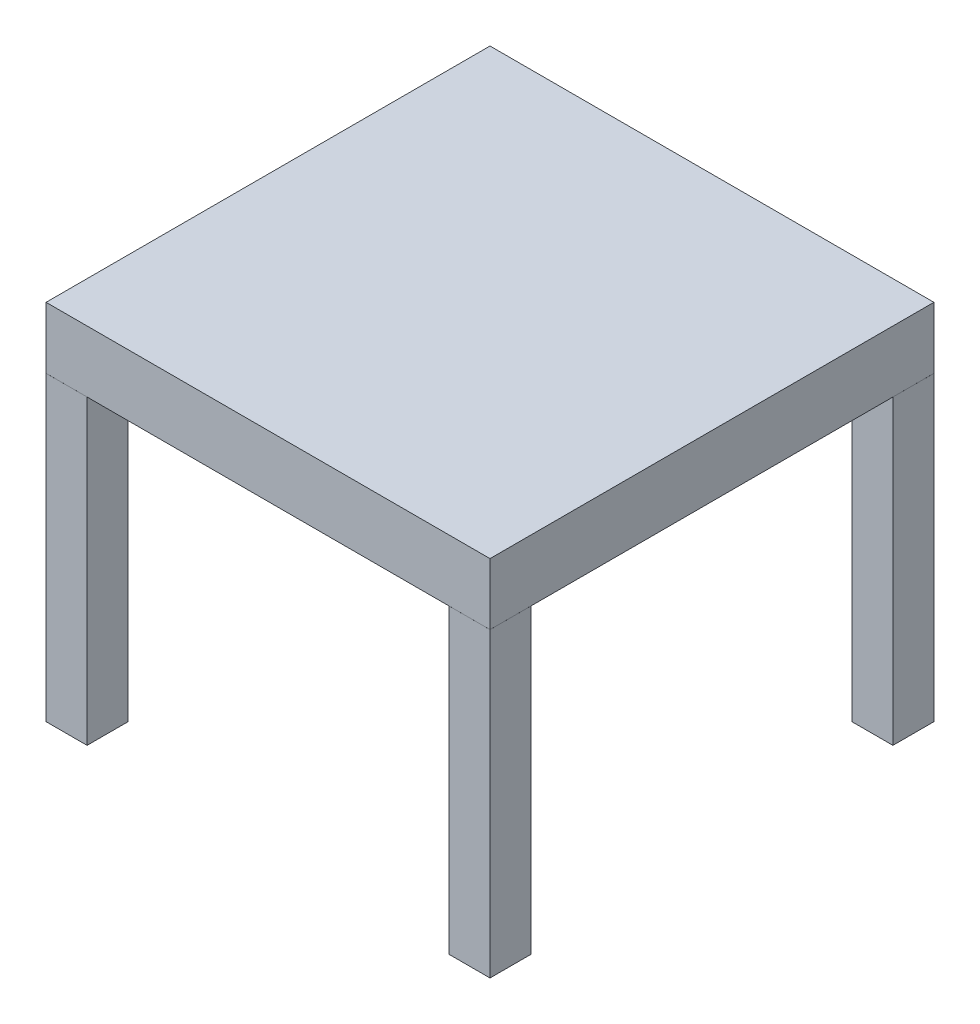
SolidWorks part; units mm, degrees
ref_plane "Front Plane" through (0, 0, 0) normal (0, 0, 1) x (1, 0, 0)
ref_plane "Top Plane" through (0, 0, 0) normal (0, 1, 0) x (1, 0, 0)
ref_plane "Right Plane" through (0, 0, 0) normal (1, 0, 0) x (0, 0, -1)
sketch "Sketch3" plane through (0, 0, 0) normal (0, 1, 0) x (1, 0, 0)
  line L0 (-275, 275) -> (275, -275) construction
  line L1 (-275, 275) -> (275, 275)
  line L2 (-275, 275) -> (-275, -275)
  line L3 (-275, -275) -> (275, -275)
  line L4 (275, 275) -> (275, -275)
  dimension "D1" = 550
extrude "Boss-Extrude2" add sketch "Sketch3" along normal mid plane 76.2
sketch "Sketch5" plane through (0, -38.1, 0) normal (0, -1, 0) x (1, 0, 0)
  line L0 (275, 0) -> (0, 0) construction
  line L1 (275, 275) -> (224.2, 275)
  line L2 (275, 275) -> (275, 224.2)
  line L3 (275, 224.2) -> (224.2, 224.2)
  line L4 (224.2, 275) -> (224.2, 224.2)
  line L5 (275, 275) -> (275, -275) construction
  line L6 (0, 0) -> (0, 275) construction
  line L7 (-275, 275) -> (275, 275) construction
  line L8 (224.2, -275) -> (224.2, -224.2)
  line L9 (275, -224.2) -> (224.2, -224.2)
  line L10 (275, -275) -> (275, -224.2)
  line L11 (275, -275) -> (224.2, -275)
  line L12 (-275, -275) -> (-224.2, -275)
  line L13 (-275, -275) -> (-275, -224.2)
  line L14 (-275, -224.2) -> (-224.2, -224.2)
  line L15 (-224.2, -275) -> (-224.2, -224.2)
  line L16 (-224.2, 275) -> (-224.2, 224.2)
  line L17 (-275, 224.2) -> (-224.2, 224.2)
  line L18 (-275, 275) -> (-275, 224.2)
  line L19 (-275, 275) -> (-224.2, 275)
  dimension "D1" = 50.8
extrude "Boss-Extrude3" add sketch "Sketch5" along normal offset from surface (373.8 mm away) 450 up to face at (0, 38.1, 0)
sketch "Sketch6" plane through (275, 0, 0) normal (1, 0, 0) x (0, 0, -1)
  line L1 (-295.1485, -38.1) -> (360.4823, -38.1)
  line L2 (-295.1485, -38.1) -> (-295.1485, -38.1254)
  line L3 (-295.1485, -38.1254) -> (360.4823, -38.1254)
  line L4 (360.4823, -38.1) -> (360.4823, -38.1254)
  dimension "D1" = 0.0254
extrude "Cut-Extrude1" cut sketch "Sketch6" against normal through all both and the other way through all
